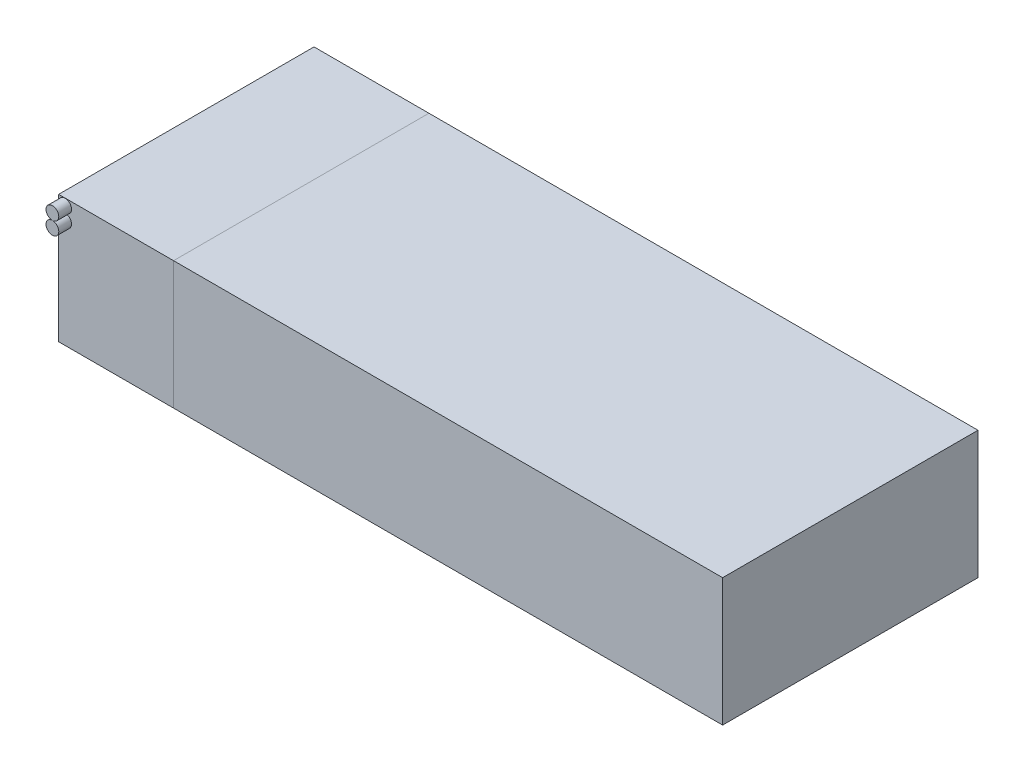
SolidWorks part; units mm, degrees
ref_plane "Front Plane" through (0, 0, 0) normal (0, 0, 1) x (1, 0, 0)
ref_plane "Top Plane" through (0, 0, 0) normal (0, 1, 0) x (1, 0, 0)
ref_plane "Right Plane" through (0, 0, 0) normal (1, 0, 0) x (0, 0, -1)
sketch "Sketch1" plane through (0, 0, 0) normal (0, 1, 0) x (1, 0, 0)
  line L1 (0, 0) -> (52, 0)
  line L2 (0, 0) -> (0, 20)
  line L3 (0, 20) -> (52, 20)
  line L4 (52, 0) -> (52, 20)
  dimension "D1" = 52
  dimension "D2" = 20
extrude "Boss-Extrude1" add sketch "Sketch1" along normal blind 10
sketch "Sketch3" plane through (0, 0, 0) normal (0, 0, 1) x (1, 0, 0)
  line L4 (0, 10) -> (52, 10) construction
  line L5 (0, 10) -> (0, 0) construction
  circle A9 centre (0.51, 8.48) radius 0.5
  circle A11 centre (0.51, 9.49) radius 0.5
  point P2 (0.6122, 9.4147)
  point P6 (0, 0)
  point P7 (0, 0)
  point P9 (0, 9.8771)
  dimension "D1" = 2
  dimension "D5" = 1.01
  dimension "D3" = 0.51
  dimension "D2" = 1
  dimension "D4" = 0.51
sketch "Sketch4" plane through (0, 0, 0) normal (0, 0, 1) x (1, 0, 0)
  line L0 (9, 10) -> (9, 0)
  line L1 (0, 10) -> (52, 10) construction
  line L2 (0, 0) -> (52, 0) construction
  line L3 (0, 10) -> (0, 0) construction
  dimension "D1" = 9
split line "Split Line1"
extrude "Boss-Extrude7" add sketch "Sketch3" along normal blind 1 contours A11 | A9
